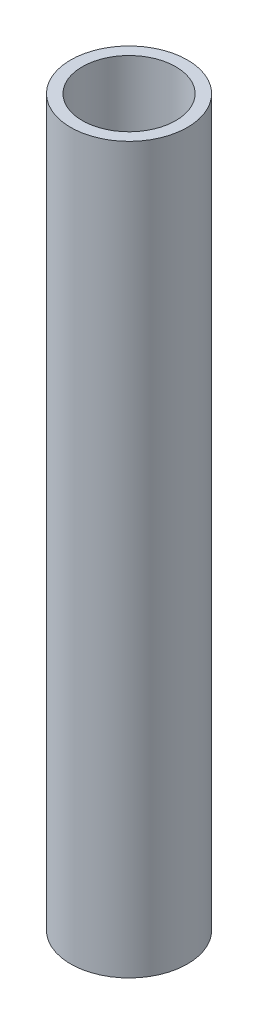
SolidWorks part; units mm, degrees
ref_plane "Front Plane" through (0, 0, 0) normal (0, 0, 1) x (1, 0, 0)
ref_plane "Top Plane" through (0, 0, 0) normal (0, 1, 0) x (1, 0, 0)
ref_plane "Right Plane" through (0, 0, 0) normal (1, 0, 0) x (0, 0, -1)
sketch "Sketch1" plane through (0, 0, 0) normal (0, 0, 1) x (1, 0, 0)
  line L0 (0, 0) -> (0, 39.359) construction
  line L1 (0, 0) -> (14.29, 0) construction
  line L2 (14.29, 0) -> (14.29, 12.5)
  line L3 (14.29, 12.5) -> (12.7, 14.09)
  line L4 (12.7, 14.09) -> (12.7, 196.85)
  line L5 (12.7, 196.85) -> (15.875, 196.85)
  line L6 (15.875, 196.85) -> (15.875, 0)
  line L7 (15.875, 0) -> (14.29, 0)
  dimension "D1" = 135
  dimension "D2" = 12.7
  dimension "D3" = 15.875
  dimension "D4" = 14.29
  dimension "D5" = 12.5
  dimension "D6" = 196.85
revolve "Revolve1" add sketch "Sketch1" angle 360 about L0
